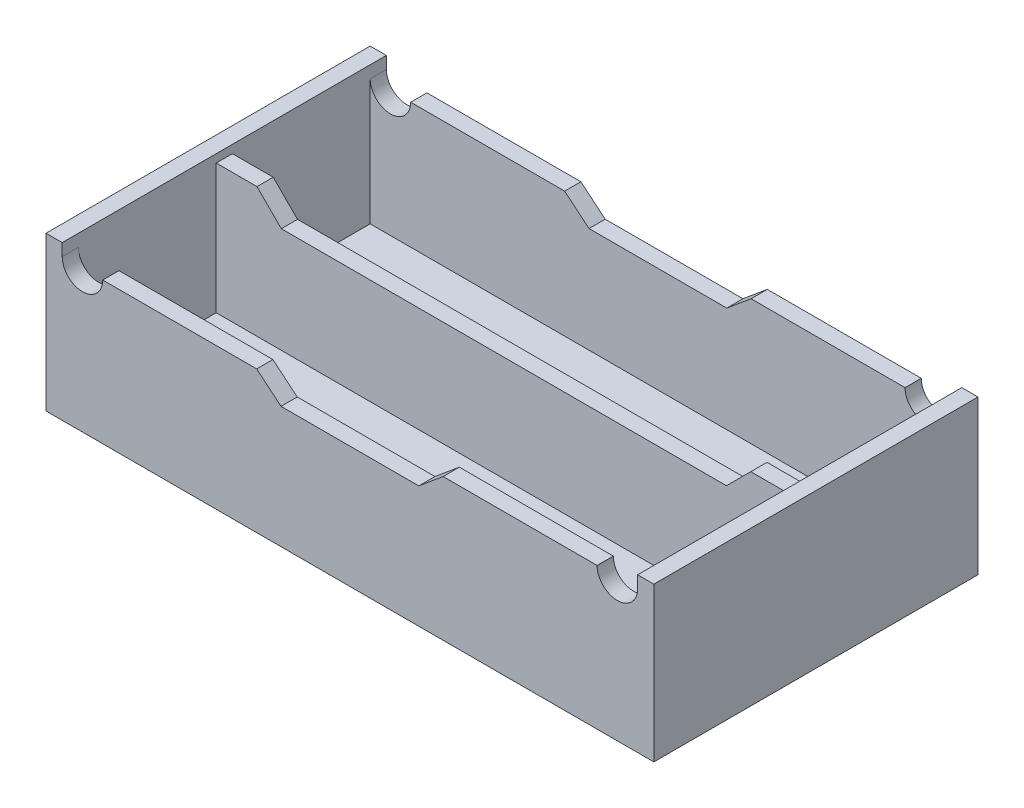
SolidWorks part; units mm, degrees
ref_plane "Front Plane" through (0, 0, 0) normal (0, 0, 1) x (1, 0, 0)
ref_plane "Top Plane" through (0, 0, 0) normal (0, 1, 0) x (1, 0, 0)
ref_plane "Right Plane" through (0, 0, 0) normal (1, 0, 0) x (0, 0, -1)
sketch "Sketch1" plane through (0, 0, 0) normal (0, 1, 0) x (1, 0, 0)
  line L1 (0, 0) -> (75, 0)
  line L2 (0, 0) -> (0, 40)
  line L3 (0, 40) -> (75, 40)
  line L4 (75, 0) -> (75, 40)
  dimension "D1" = 75
  dimension "D2" = 40
extrude "Boss-Extrude1" add sketch "Sketch1" along normal blind 2
sketch "Sketch2" plane through (0, 2, 0) normal (0, 1, 0) x (1, 0, 0)
  line L1 (2, 38) -> (73, 38)
  line L2 (2, 38) -> (2, 21)
  line L3 (2, 21) -> (73, 21)
  line L4 (73, 38) -> (73, 21)
  line L5 (2, 19) -> (73, 19)
  line L6 (2, 19) -> (2, 2)
  line L7 (2, 2) -> (73, 2)
  line L8 (73, 19) -> (73, 2)
  line L9 (0, 40) -> (75, 40)
  line L10 (0, 40) -> (0, 0)
  line L11 (0, 0) -> (75, 0)
  line L12 (75, 40) -> (75, 0)
  point P14 (0, 20)
  dimension "D1" = 2
  dimension "D2" = 2
  dimension "D3" = 2
  dimension "D4" = 2
  dimension "D5" = 2
  dimension "D6" = 1
extrude "Boss-Extrude2" add sketch "Sketch2" along normal blind 17
sketch "Sketch3" plane through (0, 0, 0) normal (0, 0, 1) x (1, 0, 0)
  line L0 (2, 17.5) -> (2, 19)
  line L1 (2, 19) -> (2, 2) construction
  line L2 (2, 19) -> (73, 19)
  line L3 (73, 19) -> (73, 17.5)
  line L4 (73, 19) -> (73, 2) construction
  line L5 (7, 17.5) -> (26, 17.5)
  line L6 (26, 17.5) -> (29, 15)
  line L7 (29, 15) -> (46, 15)
  line L8 (46, 15) -> (49, 17.5)
  line L9 (49, 17.5) -> (68, 17.5)
  arc A0 (2, 17.5) -> (7, 17.5) centre (4.5, 17.5) ccw
  arc A1 (68, 17.5) -> (73, 17.5) centre (70.5, 17.5) ccw
  point P11 (37.5, 15)
  point P13 (0, 0)
  point P21 (37.5, 19)
  dimension "D1" = 5
  dimension "D2" = 17
  dimension "D3" = 3
  dimension "D4" = 1.5
extrude "Cut-Extrude2" cut sketch "Sketch3" against normal blind 17 contours L6 L7 L8 L9 A1 L3 L2 L0 A0 L5
ref_plane "Plane1" through (0, 0, -20) normal (0, 0, 1) x (1, 0, 0)
mirror "Mirror1" about plane through (0, 0, -20) normal (0, 0, 1) of "Cut-Extrude2"
sketch "Sketch4" plane through (0, 0, -19) normal (0, 0, 1) x (1, 0, 0)
  line L0 (2, 18) -> (7.0359, 18)
  line L1 (2, 19) -> (2, 2) construction
  line L2 (7.0359, 18) -> (10.0359, 15)
  line L3 (10.0359, 15) -> (64.9641, 15)
  line L4 (64.9641, 15) -> (67.9641, 18)
  line L5 (67.9641, 18) -> (73, 18)
  line L6 (73, 19) -> (73, 2) construction
  line L7 (46, 15) -> (29, 15) construction
  line L9 (73, 19) -> (2, 19) construction
  line L10 (2, 18) -> (2, 19)
  line L11 (2, 19) -> (73, 19)
  line L12 (73, 19) -> (73, 18)
  dimension "D1" = 1
  dimension "D2" = 3
extrude "Cut-Extrude3" cut sketch "Sketch4" against normal up to next contours L2 L3 L4 L5 L12 L11 L10 L0
sketch "Sketch5" plane through (0, 2, 0) normal (0, 1, 0) x (1, 0, 0)
  line L0 (2, 38) -> (2, 21) construction
  line L1 (2, 19) -> (2, 2) construction
  line L2 (73, 38) -> (2, 38) construction
  circle A0 centre (37.5, 29.5) radius 1.6
  circle A1 centre (37.5, 10.5) radius 1.6
  point P4 (2, 29.5)
  point P5 (2, 10.5)
  point P8 (37.5, 38)
  point P11 (0, 0)
  point P14 (0, 0)
  point P15 (0, 0)
  point P16 (0, 0)
  dimension "D1" = 3.2
extrude "Cut-Extrude4" cut sketch "Sketch5" against normal up to next
